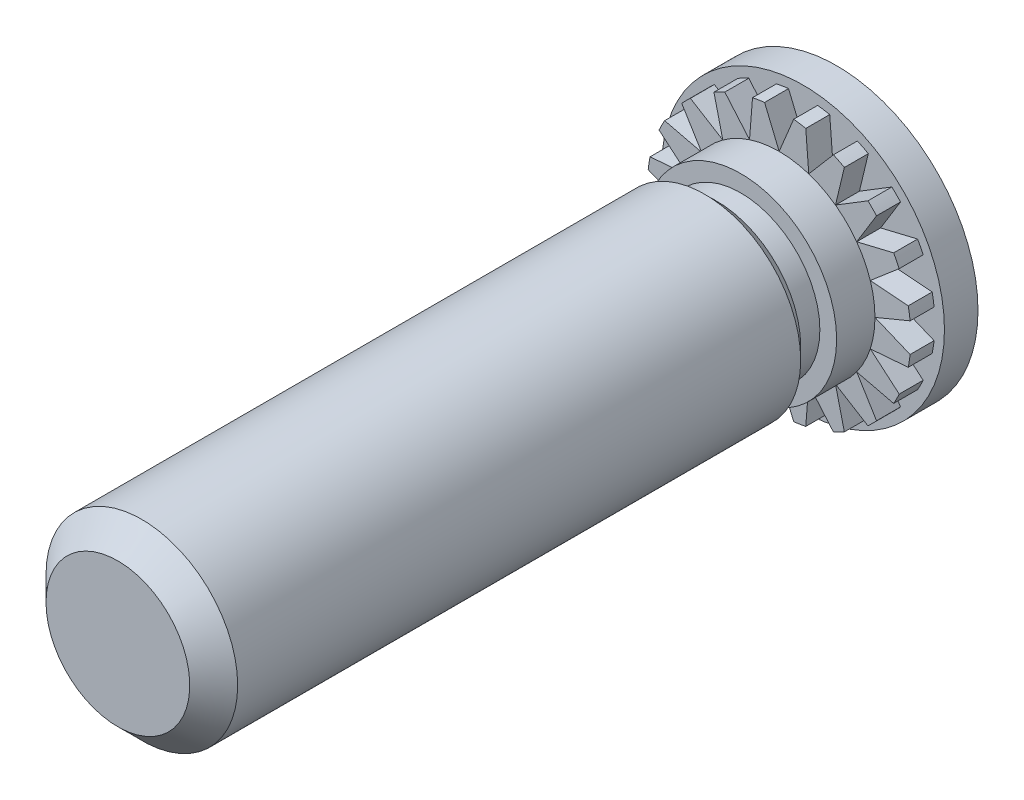
SolidWorks part; units mm, degrees
ref_plane "Спереди" through (0, 0, 0) normal (0, 0, 1) x (1, 0, 0)
ref_plane "Сверху" through (0, 0, 0) normal (0, 1, 0) x (1, 0, 0)
ref_plane "Справа" through (0, 0, 0) normal (1, 0, 0) x (0, 0, -1)
sketch "Эскиз1" plane through (0, 0, 0) normal (0, 0, 1) x (1, 0, 0)
  circle A0 centre (0, 0) radius 2.95
  dimension "D1" = 5.9
extrude "Вытянуть1" add sketch "Эскиз1" along normal blind 1.2
ref_axis "Ось1" through (0, 0, 10.6426) along (0, 0, -1)
sketch "Эскиз2" plane through (0, 0, 1.2) normal (0, 0, 1) x (1, 0, 0)
  circle A0 centre (0, 0) radius 2
  dimension "D1" = 4
extrude "Вытянуть2" add sketch "Эскиз2" along normal blind 1.9
sketch "Эскиз3" plane through (0, 0, 1.2) normal (0, 0, 1) x (1, 0, 0)
  line L0 (0, 0) -> (0, 2.95) construction
  line L1 (-0.3935, 2.95) -> (0.3935, 2.95)
  line L2 (0.3935, 2.95) -> (0, 2)
  line L3 (0, 2) -> (-0.3935, 2.95)
  circle A0 centre (0, 0) radius 2.95 construction
  circle A1 centre (0, 0) radius 2 construction
  dimension "D1" = 45
extrude "Вырез-Вытянуть1" cut sketch "Эскиз3" against normal blind 0.5
pattern_circular "Круговой массив1" count 20 over 360 about axis through (0, 0, 0) along (0, 0, 1) of "Вырез-Вытянуть1"
sketch "Эскиз4" plane through (0, 0, 0) normal (0, 1, 0) x (1, 0, 0)
  line L0 (0, -2.25) -> (2, -2.25) construction
  line L1 (0, -10.6426) -> (0, 0.6656) construction
  line L2 (-2, -3.1) -> (2, -3.1) construction
  line L3 (2, -2) -> (1.65, -2)
  line L4 (2, -2) -> (2, -2.5)
  line L5 (2, -2.5) -> (1.65, -2.5)
  line L6 (1.65, -2) -> (1.65, -2.5)
  dimension "D1" = 0.5
  dimension "D2" = 0.6
  dimension "D3" = 2
  dimension "D4" = 0.35
revolve "Вырез-Повернуть1" cut sketch "Эскиз4" angle 360 about axis through (0, 0, 10.6426) along (0, 0, -1)
sketch "Эскиз6" plane through (0, 0, 0) normal (1, 0, 0) x (0, 0, -1)
  line L0 (-3.1, 0) -> (-15, 0)
  line L1 (-3.1, 2) -> (-3.1, -2) construction
  line L2 (-10.6426, 0) -> (0.6656, 0) construction
  line L3 (-15, 0) -> (-15, -2)
  line L4 (-15, -2) -> (-3.1, -2)
  line L5 (-3.1, -2) -> (-3.1, 0)
  line L6 (0, -2.95) -> (0, 2.95) construction
  dimension "D1" = 15
  dimension "D2" = 2
revolve "Повернуть1" add sketch "Эскиз6" angle 360 about L0
chamfer "Фаска2" distance 0.5 angle 45 1 edges at (-2, 0, 15)
sketch "Эскиз7" plane through (0, 0, 1.2) normal (0, 0, 1) x (1, 0, 0)
  circle A0 centre (0, 0) radius 2.75
  circle A1 centre (0, 0) radius 2.95
  arc A2 (-1.4093, 2.5916) -> (-2.0293, 2.1412) centre (0, 0) ccw construction
  dimension "D1" = 0.2
extrude "Вырез-Вытянуть2" cut sketch "Эскиз7" against normal up to surface (0.5 mm away) up to face at (-2.4965, 0.8112, 0.7)
chamfer "Фаска3" distance 0.25 angle 45 1 edges at (2, 0, 2.5)
